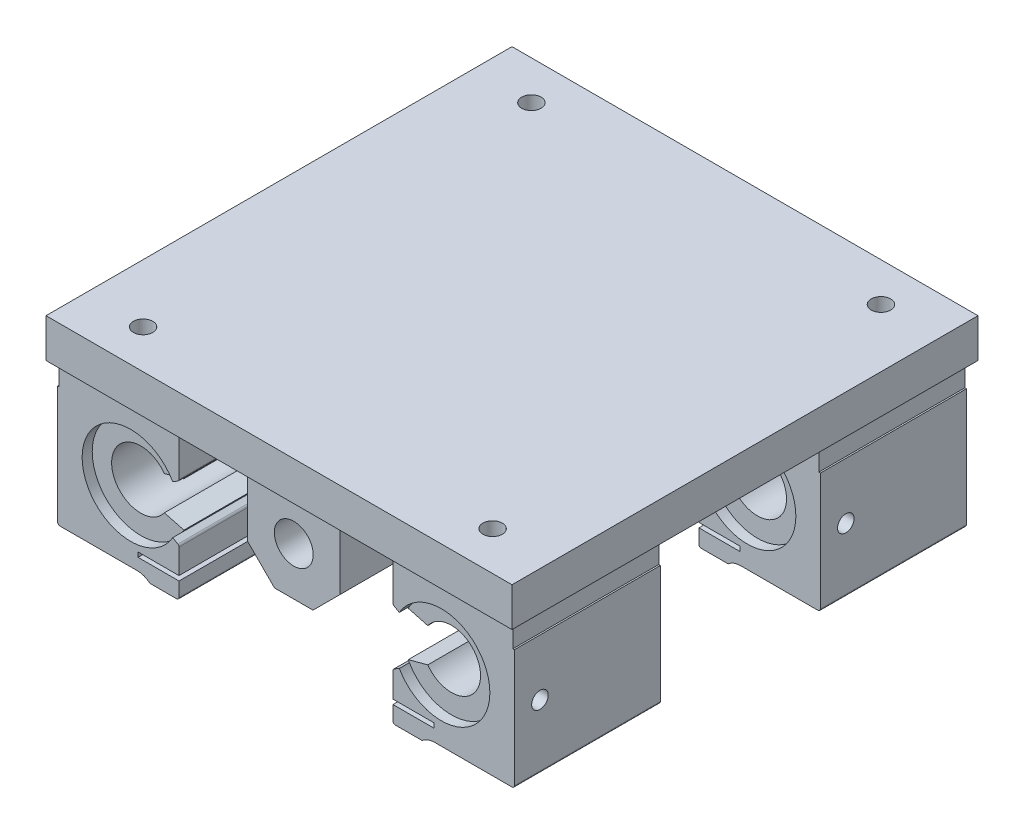
SolidWorks part; units mm, degrees
material "1060 Alloy"
ref_plane "Front" through (0, 0, 0) normal (0, 0, 1) x (1, 0, 0)
ref_plane "Top" through (0, 0, 0) normal (0, 1, 0) x (1, 0, 0)
ref_plane "Right" through (0, 0, 0) normal (1, 0, 0) x (0, 0, -1)
sketch "Sketch21" plane through (0, 0, 0) normal (0, 0, 1) x (1, 0, 0)
  line L0 (76.2, 16.1798) -> (76.2, 28.8798)
  line L1 (76.2, 28.8798) -> (-76.2, 28.8798)
  line L2 (-76.2, 28.8798) -> (-76.2, 16.1798)
  line L3 (-76.2, 16.1798) -> (76.2, 16.1798)
  line L4 (-43.0635, -2.0638) -> (-36.6851, -0.3547)
  line L5 (-36.6851, -14.8853) -> (-43.0635, -13.1762)
  line L6 (0, 0) -> (0, -5.0153) construction
  line L8 (-73.914, -30.7086) -> (-48.6405, -30.7086)
  line L9 (-44.5135, -32.2326) -> (-35.7505, -32.2326)
  line L10 (-34.9885, -31.4706) -> (-34.9885, -26.797)
  line L11 (-34.9885, -26.797) -> (-48.387, -26.797)
  line L12 (-48.387, -26.797) -> (-48.387, -25.273)
  line L13 (-48.387, -25.273) -> (-34.9885, -25.273)
  line L14 (-34.9885, -25.273) -> (-34.9885, -17.1887)
  line L15 (-35.3695, -16.5288) -> (-37.0518, -15.5575)
  line L16 (-37.0518, 0.3175) -> (-35.3695, 1.2888)
  line L17 (-34.9885, 1.9487) -> (-34.9885, 15.4178)
  line L18 (-35.7505, 16.1798) -> (-74.168, 16.1798)
  line L19 (-74.168, 16.1798) -> (-74.168, 8.5598)
  line L20 (-74.168, 8.5598) -> (-74.676, 8.5598)
  line L21 (-74.676, 8.5598) -> (-74.676, -29.9466)
  line L22 (15.1765, -6.8072) -> (15.1765, 15.5448)
  line L23 (15.1765, 15.5448) -> (-15.1765, 15.5448)
  line L24 (-15.1765, 15.5448) -> (-15.1765, -6.8072)
  line L25 (-15.1765, -6.8072) -> (-6.2865, -15.6972)
  line L26 (-6.2865, -15.6972) -> (6.2865, -15.6972)
  line L27 (6.2865, -15.6972) -> (15.1765, -6.8072)
  line L28 (74.676, -29.9466) -> (74.676, 8.5598)
  line L29 (74.676, 8.5598) -> (74.168, 8.5598)
  line L30 (74.168, 8.5598) -> (74.168, 16.1798)
  line L31 (74.168, 16.1798) -> (35.7505, 16.1798)
  line L32 (34.9885, 15.4178) -> (34.9885, 1.9487)
  line L33 (35.3695, 1.2888) -> (37.0518, 0.3175)
  line L34 (37.0518, -15.5575) -> (35.3695, -16.5288)
  line L35 (34.9885, -17.1887) -> (34.9885, -25.273)
  line L36 (34.9885, -25.273) -> (48.387, -25.273)
  line L37 (48.387, -25.273) -> (48.387, -26.797)
  line L38 (48.387, -26.797) -> (34.9885, -26.797)
  line L39 (34.9885, -26.797) -> (34.9885, -31.4706)
  line L40 (35.7505, -32.2326) -> (44.5135, -32.2326)
  line L41 (48.6405, -30.7086) -> (73.914, -30.7086)
  circle A0 centre (0, 0) radius 7.9375
  arc A2 (-36.6851, -0.3547) -> (-36.6851, -14.8853) centre (-50.8, -7.62) ccw
  arc A3 (-43.0635, -2.0638) -> (-43.0635, -13.1762) centre (-50.8, -7.62) ccw
  arc A4 (-74.676, -29.9466) -> (-73.914, -30.7086) centre (-73.914, -29.9466) ccw
  arc A5 (-44.5135, -32.2326) -> (-48.6405, -30.7086) centre (-48.6405, -37.0586) ccw
  arc A6 (-35.7505, -32.2326) -> (-34.9885, -31.4706) centre (-35.7505, -31.4706) ccw
  arc A7 (-34.9885, -17.1887) -> (-35.3695, -16.5288) centre (-35.7505, -17.1887) ccw
  arc A8 (-37.0518, 0.3175) -> (-37.0518, -15.5575) centre (-50.8, -7.62) ccw
  arc A9 (-35.3695, 1.2888) -> (-34.9885, 1.9487) centre (-35.7505, 1.9487) ccw
  arc A10 (-34.9885, 15.4178) -> (-35.7505, 16.1798) centre (-35.7505, 15.4178) ccw
  arc A13 (35.7505, 16.1798) -> (34.9885, 15.4178) centre (35.7505, 15.4178) ccw
  arc A22 (34.9885, 1.9487) -> (35.3695, 1.2888) centre (35.7505, 1.9487) ccw
  arc A24 (37.0518, -15.5575) -> (37.0518, 0.3175) centre (50.8, -7.62) ccw
  arc A25 (35.3695, -16.5288) -> (34.9885, -17.1887) centre (35.7505, -17.1887) ccw
  arc A26 (34.9885, -31.4706) -> (35.7505, -32.2326) centre (35.7505, -31.4706) ccw
  arc A27 (48.6405, -30.7086) -> (44.5135, -32.2326) centre (48.6405, -37.0586) ccw
  arc A28 (73.914, -30.7086) -> (74.676, -29.9466) centre (73.914, -29.9466) ccw
  dimension "D1" = 15.875
  dimension "D2" = 9.525
  dimension "D3" = 0.762
  dimension "D4" = 15.875
  dimension "D6" = 15.875
  dimension "D7" = 6.35
  dimension "D8" = 0.762
  dimension "D9" = 1.524
  dimension "D10" = 2.032
  dimension "D11" = 25.4
  dimension "D12" = 27.5595
  dimension "D13" = 27.813
  dimension "D14" = 33.1365
  dimension "D15" = 39.1482
  dimension "D16" = 40.8305
  dimension "D17" = 41.2115
  dimension "D18" = 111.1885
  dimension "D19" = 120.7135
  dimension "D30" = 21.3614
  dimension "D32" = 15.875
  dimension "D33" = 30
  dimension "D20" = 61.0235
  dimension "D21" = 69.9135
  dimension "D22" = 76.2
  dimension "D23" = 82.4865
  dimension "D24" = 91.3765
  dimension "D25" = 124.8405
  dimension "D26" = 10.2616
  dimension "D27" = 11.7856
  dimension "D28" = 19.8699
  dimension "D29" = 12.7
  dimension "D31" = 124.587
  dimension "D34" = 150.368
  dimension "D35" = 150.876
  dimension "D36" = 152.4
  dimension "D39" = 30.2514
  dimension "D42" = 37.0586
  dimension "D46" = 45.6184
  dimension "D47" = 52.6034
  dimension "D49" = 65.9384
sketch "Sketch2" plane through (0, 0, 0) normal (0, 0, 1) x (1, 0, 0)
  line L4 (76.2, 16.1798) -> (76.2, 28.8798)
  line L5 (-76.2, 16.1798) -> (76.2, 16.1798)
  line L6 (-76.2, 28.8798) -> (-76.2, 16.1798)
  line L7 (76.2, 28.8798) -> (-76.2, 28.8798)
  line L8 (76.2, 16.1798) -> (76.2, 28.8798)
  line L9 (-76.2, 16.1798) -> (76.2, 16.1798)
  line L10 (-76.2, 28.8798) -> (-76.2, 16.1798)
  line L11 (76.2, 28.8798) -> (-76.2, 28.8798)
  dimension "D1" = 0
extrude "Extrude1" add sketch "Sketch2" along normal mid plane 152.4
ref_plane "Plane1" through (0, 0, 73.914) normal (0, 0, 1) x (1, 0, 0)
sketch "Sketch22" plane through (0, 0, 73.914) normal (0, 0, 1) x (1, 0, 0)
  line L14 (-74.168, 8.5598) -> (-74.676, 8.5598)
  line L15 (-74.168, 16.1798) -> (-74.168, 8.5598)
  line L16 (-35.7505, 16.1798) -> (-74.168, 16.1798)
  line L17 (-34.9885, 1.9487) -> (-34.9885, 15.4178)
  line L18 (-37.0518, 0.3175) -> (-35.3695, 1.2888)
  line L19 (-35.3695, -16.5288) -> (-37.0518, -15.5575)
  line L20 (-34.9885, -25.273) -> (-34.9885, -17.1887)
  line L21 (-48.387, -25.273) -> (-34.9885, -25.273)
  line L22 (-48.387, -26.797) -> (-48.387, -25.273)
  line L23 (-34.9885, -26.797) -> (-48.387, -26.797)
  line L24 (-34.9885, -31.4706) -> (-34.9885, -26.797)
  line L25 (-44.5135, -32.2326) -> (-35.7505, -32.2326)
  line L26 (-73.914, -30.7086) -> (-48.6405, -30.7086)
  line L27 (-74.676, 8.5598) -> (-74.676, -29.9466)
  line L28 (-74.168, 8.5598) -> (-74.676, 8.5598)
  line L29 (-74.168, 16.1798) -> (-74.168, 8.5598)
  line L30 (-35.7505, 16.1798) -> (-74.168, 16.1798)
  line L31 (-34.9885, 1.9487) -> (-34.9885, 15.4178)
  line L32 (-37.0518, 0.3175) -> (-35.3695, 1.2888)
  line L33 (-35.3695, -16.5288) -> (-37.0518, -15.5575)
  line L34 (-34.9885, -25.273) -> (-34.9885, -17.1887)
  line L35 (-48.387, -25.273) -> (-34.9885, -25.273)
  line L36 (-48.387, -26.797) -> (-48.387, -25.273)
  line L37 (-34.9885, -26.797) -> (-48.387, -26.797)
  line L38 (-34.9885, -31.4706) -> (-34.9885, -26.797)
  line L39 (-44.5135, -32.2326) -> (-35.7505, -32.2326)
  line L40 (-73.914, -30.7086) -> (-48.6405, -30.7086)
  line L41 (-74.676, 8.5598) -> (-74.676, -29.9466)
  line L42 (37.0518, -15.5575) -> (35.3695, -16.5288)
  line L43 (34.9885, -17.1887) -> (34.9885, -25.273)
  line L44 (34.9885, -25.273) -> (48.387, -25.273)
  line L45 (48.387, -25.273) -> (48.387, -26.797)
  line L46 (48.387, -26.797) -> (34.9885, -26.797)
  line L47 (34.9885, -26.797) -> (34.9885, -31.4706)
  line L48 (35.7505, -32.2326) -> (44.5135, -32.2326)
  line L49 (48.6405, -30.7086) -> (73.914, -30.7086)
  line L50 (74.676, -29.9466) -> (74.676, 8.5598)
  line L51 (74.676, 8.5598) -> (74.168, 8.5598)
  line L52 (74.168, 8.5598) -> (74.168, 16.1798)
  line L53 (74.168, 16.1798) -> (35.7505, 16.1798)
  line L54 (34.9885, 15.4178) -> (34.9885, 1.9487)
  line L55 (35.3695, 1.2888) -> (37.0518, 0.3175)
  line L56 (37.0518, -15.5575) -> (35.3695, -16.5288)
  line L57 (34.9885, -17.1887) -> (34.9885, -25.273)
  line L58 (34.9885, -25.273) -> (48.387, -25.273)
  line L59 (48.387, -25.273) -> (48.387, -26.797)
  line L60 (48.387, -26.797) -> (34.9885, -26.797)
  line L61 (34.9885, -26.797) -> (34.9885, -31.4706)
  line L62 (35.7505, -32.2326) -> (44.5135, -32.2326)
  line L63 (48.6405, -30.7086) -> (73.914, -30.7086)
  line L64 (74.676, -29.9466) -> (74.676, 8.5598)
  line L65 (74.676, 8.5598) -> (74.168, 8.5598)
  line L66 (74.168, 8.5598) -> (74.168, 16.1798)
  line L67 (74.168, 16.1798) -> (35.7505, 16.1798)
  line L68 (34.9885, 15.4178) -> (34.9885, 1.9487)
  line L69 (35.3695, 1.2888) -> (37.0518, 0.3175)
  arc A8 (-34.9885, 15.4178) -> (-35.7505, 16.1798) centre (-35.7505, 15.4178) ccw
  arc A9 (-35.3695, 1.2888) -> (-34.9885, 1.9487) centre (-35.7505, 1.9487) ccw
  arc A10 (-37.0518, 0.3175) -> (-37.0518, -15.5575) centre (-50.8, -7.62) ccw
  arc A11 (-34.9885, -17.1887) -> (-35.3695, -16.5288) centre (-35.7505, -17.1887) ccw
  arc A12 (-35.7505, -32.2326) -> (-34.9885, -31.4706) centre (-35.7505, -31.4706) ccw
  arc A13 (-44.5135, -32.2326) -> (-48.6405, -30.7086) centre (-48.6405, -37.0586) ccw
  arc A14 (-74.676, -29.9466) -> (-73.914, -30.7086) centre (-73.914, -29.9466) ccw
  arc A15 (-34.9885, 15.4178) -> (-35.7505, 16.1798) centre (-35.7505, 15.4178) ccw
  arc A16 (-35.3695, 1.2888) -> (-34.9885, 1.9487) centre (-35.7505, 1.9487) ccw
  arc A17 (-37.0518, 0.3175) -> (-37.0518, -15.5575) centre (-50.8, -7.62) ccw
  arc A18 (-34.9885, -17.1887) -> (-35.3695, -16.5288) centre (-35.7505, -17.1887) ccw
  arc A19 (-35.7505, -32.2326) -> (-34.9885, -31.4706) centre (-35.7505, -31.4706) ccw
  arc A20 (-44.5135, -32.2326) -> (-48.6405, -30.7086) centre (-48.6405, -37.0586) ccw
  arc A21 (-74.676, -29.9466) -> (-73.914, -30.7086) centre (-73.914, -29.9466) ccw
  arc A22 (35.3695, -16.5288) -> (34.9885, -17.1887) centre (35.7505, -17.1887) ccw
  arc A23 (34.9885, -31.4706) -> (35.7505, -32.2326) centre (35.7505, -31.4706) ccw
  arc A24 (48.6405, -30.7086) -> (44.5135, -32.2326) centre (48.6405, -37.0586) ccw
  arc A25 (73.914, -30.7086) -> (74.676, -29.9466) centre (73.914, -29.9466) ccw
  arc A26 (35.7505, 16.1798) -> (34.9885, 15.4178) centre (35.7505, 15.4178) ccw
  arc A27 (34.9885, 1.9487) -> (35.3695, 1.2888) centre (35.7505, 1.9487) ccw
  arc A28 (37.0518, -15.5575) -> (37.0518, 0.3175) centre (50.8, -7.62) ccw
  arc A29 (35.3695, -16.5288) -> (34.9885, -17.1887) centre (35.7505, -17.1887) ccw
  arc A30 (34.9885, -31.4706) -> (35.7505, -32.2326) centre (35.7505, -31.4706) ccw
  arc A31 (48.6405, -30.7086) -> (44.5135, -32.2326) centre (48.6405, -37.0586) ccw
  arc A32 (73.914, -30.7086) -> (74.676, -29.9466) centre (73.914, -29.9466) ccw
  arc A33 (35.7505, 16.1798) -> (34.9885, 15.4178) centre (35.7505, 15.4178) ccw
  arc A34 (34.9885, 1.9487) -> (35.3695, 1.2888) centre (35.7505, 1.9487) ccw
  arc A35 (37.0518, -15.5575) -> (37.0518, 0.3175) centre (50.8, -7.62) ccw
  dimension "D1" = 0
  dimension "D2" = 0
extrude "Extrude2" add sketch "Sketch22" against normal blind 47.752
mirror "Mirror2" about plane through (0, 0, 0) normal (0, 0, 1) of "Extrude2"
sketch "Sketch23" plane through (5.3677, 28.8798, -305.8138) normal (0, 1, 0) x (-1, 0, 0)
  line L1 (-70.8323, 382.0138) -> (81.5677, 382.0138) construction
  line L4 (-70.8323, 382.0138) -> (-70.8323, 229.6138) construction
  circle A0 centre (62.5177, 369.3138) radius 3.175
  circle A1 centre (62.5177, 242.3138) radius 3.175
  circle A2 centre (-51.7823, 242.3138) radius 3.175
  circle A3 centre (-51.7823, 369.3138) radius 3.175
  dimension "D4" = 6.35
  dimension "D5" = 114.3
  dimension "D6" = 127
  dimension "D7" = 12.7
  dimension "D8" = 19.05
extrude "Cut-Extrude1" cut sketch "Sketch23" against normal blind 12.7
ref_plane "Plane2" through (0, 0, 71.374) normal (0, 0, 1) x (1, 0, 0)
sketch "Sketch24" plane through (0, 0, 71.374) normal (0, 0, 1) x (1, 0, 0)
  line L0 (-76.2, 16.1798) -> (76.2, 16.1798) construction
  line L1 (-15.1765, 16.1798) -> (15.1765, 16.1798)
  line L6 (-15.1765, 15.5448) -> (-15.1765, -6.8072)
  line L7 (15.1765, 15.5448) -> (-15.1765, 15.5448)
  line L8 (15.1765, -6.8072) -> (15.1765, 15.5448)
  line L9 (6.2865, -15.6972) -> (15.1765, -6.8072)
  line L10 (-6.2865, -15.6972) -> (6.2865, -15.6972)
  line L11 (-15.1765, -6.8072) -> (-6.2865, -15.6972)
  line L12 (-15.1765, 16.1798) -> (-15.1765, -6.8072)
  line L14 (15.1765, -6.8072) -> (15.1765, 16.1798)
  line L15 (6.2865, -15.6972) -> (15.1765, -6.8072)
  line L16 (-6.2865, -15.6972) -> (6.2865, -15.6972)
  line L17 (-15.1765, -6.8072) -> (-6.2865, -15.6972)
  circle A1 centre (0, 0) radius 7.9375 construction
  circle A2 centre (0, 0) radius 7.9375
  dimension "D1" = 0
sketch "Sketch26" plane through (0, 0, 0) normal (0, 0, 1) x (1, 0, 0)
  line L1 (76.2, 25.8826) -> (90.17, 25.8826)
  line L2 (76.2, 16.3576) -> (90.17, 16.3576)
  line L3 (90.17, 25.8826) -> (90.17, 16.3576)
  line L4 (76.2, 25.8826) -> (76.2, 16.3576)
  circle A0 centre (0, 0) radius 7.9375 construction
  dimension "D1" = 15.875
  dimension "D2" = 76.2
  dimension "D3" = 90.17
  dimension "D4" = 16.3576
  dimension "D5" = 25.8826
extrude "Extrude3" [suppressed] add sketch "Sketch26" along normal mid plane 75.438
chamfer "Chamfer1" [suppressed] distance 2.54 angle 45
sketch "Sketch27" [suppressed] plane through (90.17, 0, 0) normal (1, 0, 0) x (0, 0, -1)
  line L0 (0, 0) -> (0, -6.7645) construction
  line L1 (37.719, 20.8026) -> (27.2273, 20.8026) construction
  line L3 (-37.719, 25.8826) -> (37.719, 25.8826) construction
  circle A0 centre (-19.05, 20.8026) radius 3.937
  circle A1 centre (19.05, 20.8026) radius 3.937
  dimension "D2" = 7.874
  dimension "D1" = 38.1
  dimension "D3" = 5.08
extrude "Cut-Extrude4" [suppressed] cut sketch "Sketch27" against normal blind 12.7
sketch "Sketch29" plane through (-74.676, 0, 0) normal (-1, 0, 0) x (0, 0, 1)
  line L0 (76.2, 28.8798) -> (-76.2, 28.8798) construction
  line L1 (0, 28.8798) -> (0, -30.8828) construction
  circle A0 centre (65.532, -9.8298) radius 2.7051
  circle A1 centre (-34.4932, -9.8298) radius 2.7051
  dimension "D1" = 5.4102
  dimension "D3" = 34.4932
  dimension "D2" = 5.4102
  dimension "D6" = 38.7096
  dimension "D4" = 100.0252
  dimension "D5" = 59.7626
extrude "Cut-Extrude6" cut sketch "Sketch29" against normal blind 12.7
mirror "Mirror1" about plane through (0, 0, 0) normal (1, 0, 0) of "Cut-Extrude6"
extrude "Extrude4" add sketch "Sketch24" against normal blind 38.1
ref_plane "Plane3" through (0, 0, 70.612) normal (0, 0, 1) x (1, 0, 0)
sketch "Sketch30" plane through (0, 0, 70.612) normal (0, 0, 1) x (1, 0, 0)
  line L0 (0, 0) -> (0, -19.7458) construction
  line L1 (36.6851, -14.8853) -> (43.0635, -13.1762)
  line L2 (-43.0635, -2.0638) -> (-36.6851, -0.3547)
  line L3 (-36.6851, -14.8853) -> (-43.0635, -13.1762)
  line L4 (-43.0635, -2.0638) -> (-36.6851, -0.3547)
  line L5 (-36.6851, -14.8853) -> (-43.0635, -13.1762)
  line L6 (43.0635, -2.0638) -> (36.6851, -0.3547)
  arc A0 (43.0635, -2.0638) -> (43.0635, -13.1762) centre (50.8, -7.62) cw
  arc A1 (36.6851, -0.3547) -> (36.6851, -14.8853) centre (50.8, -7.62) cw
  arc A2 (-36.6851, -0.3547) -> (-36.6851, -14.8853) centre (-50.8, -7.62) ccw
  arc A3 (-43.0635, -2.0638) -> (-43.0635, -13.1762) centre (-50.8, -7.62) ccw
  arc A4 (-36.6851, -0.3547) -> (-36.6851, -14.8853) centre (-50.8, -7.62) ccw
  arc A5 (-43.0635, -2.0638) -> (-43.0635, -13.1762) centre (-50.8, -7.62) ccw
  dimension "D1" = 0
extrude "Extrude5" add sketch "Sketch30" against normal offset from surface (41.148 mm away) 3.302 up to face at (48.4265, -12.9548, 26.162)
ref_plane "Plane4" through (0, 0, -70.612) normal (0, 0, -1) x (-1, 0, 0)
sketch "Sketch32" plane through (0, 0, -70.612) normal (0, 0, -1) x (-1, 0, 0)
  line L2 (-43.0635, -2.0638) -> (-36.6851, -0.3547)
  line L3 (-36.6851, -14.8853) -> (-43.0635, -13.1762)
  line L4 (-43.0635, -2.0638) -> (-36.6851, -0.3547)
  line L5 (-36.6851, -14.8853) -> (-43.0635, -13.1762)
  line L6 (43.0635, -13.1762) -> (36.6851, -14.8853)
  line L7 (36.6851, -0.3547) -> (43.0635, -2.0638)
  line L8 (43.0635, -13.1762) -> (36.6851, -14.8853)
  line L9 (36.6851, -0.3547) -> (43.0635, -2.0638)
  arc A4 (-43.0635, -2.0638) -> (-43.0635, -13.1762) centre (-50.8, -7.62) ccw
  arc A5 (-36.6851, -0.3547) -> (-37.0518, 0.3175) centre (-50.8, -7.62) ccw
  arc A6 (-37.0518, 0.3175) -> (-37.0518, -15.5575) centre (-50.8, -7.62) ccw
  arc A7 (-37.0518, -15.5575) -> (-36.6851, -14.8853) centre (-50.8, -7.62) ccw
  arc A8 (-43.0635, -2.0638) -> (-43.0635, -13.1762) centre (-50.8, -7.62) ccw
  arc A9 (-36.6851, -0.3547) -> (-37.0518, 0.3175) centre (-50.8, -7.62) ccw
  arc A10 (-37.0518, 0.3175) -> (-37.0518, -15.5575) centre (-50.8, -7.62) ccw
  arc A11 (-37.0518, -15.5575) -> (-36.6851, -14.8853) centre (-50.8, -7.62) ccw
  arc A12 (43.0635, -13.1762) -> (43.0635, -2.0638) centre (50.8, -7.62) ccw
  arc A13 (36.6851, -14.8853) -> (37.0518, -15.5575) centre (50.8, -7.62) ccw
  arc A14 (37.0518, -15.5575) -> (37.0518, 0.3175) centre (50.8, -7.62) ccw
  arc A15 (37.0518, 0.3175) -> (36.6851, -0.3547) centre (50.8, -7.62) ccw
  arc A16 (43.0635, -13.1762) -> (43.0635, -2.0638) centre (50.8, -7.62) ccw
  arc A17 (36.6851, -14.8853) -> (37.0518, -15.5575) centre (50.8, -7.62) ccw
  arc A18 (37.0518, -15.5575) -> (37.0518, 0.3175) centre (50.8, -7.62) ccw
  arc A19 (37.0518, 0.3175) -> (36.6851, -0.3547) centre (50.8, -7.62) ccw
  dimension "D1" = 0
  dimension "D2" = 0
extrude "Extrude6" add sketch "Sketch32" against normal offset from surface (41.148 mm away) 3.302 up to face at (48.4265, -12.9548, -26.162)
sketch "Sketch33" plane through (0, -32.2326, 0) normal (0, -1, 0) x (1, 0, 0)
  line L0 (-64.4367, 0) -> (62.303, 0) construction
  line L1 (0, 56.7605) -> (0, -17.2645) construction
  circle A0 centre (50.8, 67.5386) radius 1.5875
  circle A1 centre (39.751, 50.0126) radius 2.0193
  circle A2 centre (-50.8, 32.4866) radius 1.5875
  circle A3 centre (-39.751, 50.0126) radius 2.0193
  circle A4 centre (50.8, -32.5374) radius 1.5875
  circle A5 centre (39.751, -50.0634) radius 2.0193
  circle A6 centre (-50.8, -67.5386) radius 1.5875
  circle A7 centre (-39.751, -50.0126) radius 2.0193
  dimension "D1" = 3.175
  dimension "D2" = 3.175
  dimension "D3" = 4.0386
  dimension "D4" = 4.0386
  dimension "D5" = 3.175
  dimension "D6" = 3.175
  dimension "D7" = 4.0386
  dimension "D8" = 4.0386
  dimension "D9" = 11.049
  dimension "D10" = 50.8
  dimension "D11" = 90.551
  dimension "D12" = 101.6
  dimension "D13" = 17.526
  dimension "D14" = 35.052
  dimension "D15" = 67.5386
  dimension "D16" = 100.076
  dimension "D17" = 117.5512
  dimension "D18" = 117.602
  dimension "D19" = 135.0772
extrude "Cut-Extrude7" cut sketch "Sketch33" against normal blind 3.302
combine bodies "Combine1" operation type add bodies to combine 135 132
sketch "Sketch34" plane through (0, 0, 71.374) normal (0, 0, 1) x (1, 0, 0)
  circle A0 centre (0, 0) radius 7.9375 construction
  circle A1 centre (0, 0) radius 7.9375
  circle A2 centre (0, 0) radius 6.35
  dimension "D1" = 12.7
extrude "Extrude7" add sketch "Sketch34" against normal up to surface (38.1 mm away) up to face at (7.9375, 0, 33.274)
sketch "Sketch37" plane through (0, 28.8798, 0) normal (0, 1, 0) x (1, 0, 0)
  line L1 (88.9, -88.9) -> (-88.9, -88.9)
  line L2 (88.9, -88.9) -> (88.9, 88.9)
  line L3 (88.9, 88.9) -> (-88.9, 88.9)
  line L4 (-88.9, -88.9) -> (-88.9, 88.9)
  line L5 (88.9, -88.9) -> (-88.9, 88.9) construction
  line L6 (88.9, 88.9) -> (-88.9, -88.9) construction
  point P0 (0, 0)
  dimension "D1" = 177.8
extrude "Boss-Extrude1" [suppressed] add sketch "Sketch37" along normal blind 12.7 contours L3 L4 L1 L2
sketch "Sketch39" [suppressed] plane through (0, 0, 0) normal (0, 0, 1) x (1, 0, 0)
  line L0 (-63.5, 41.5798) -> (63.5, 41.5798)
  line L1 (-63.5, 41.5798) -> (-25.4, 117.7798)
  line L2 (-25.4, 117.7798) -> (25.4, 117.7798)
  line L3 (25.4, 117.7798) -> (63.5, 41.5798)
  line L4 (0, 117.7798) -> (0, 41.5798) construction
  line L5 (88.9, 41.5798) -> (-88.9, 41.5798) construction
  circle A0 centre (0, 92.3798) radius 12.7
  point P3 (0, 41.5798)
  dimension "D5" = 25.4
  dimension "D4" = 25.4
  dimension "D1" = 127
  dimension "D2" = 76.2
  dimension "D3" = 50.8
extrude "Boss-Extrude2" [suppressed] add sketch "Sketch39" along normal mid plane 76.2 contours L1 L2 L3 L0
